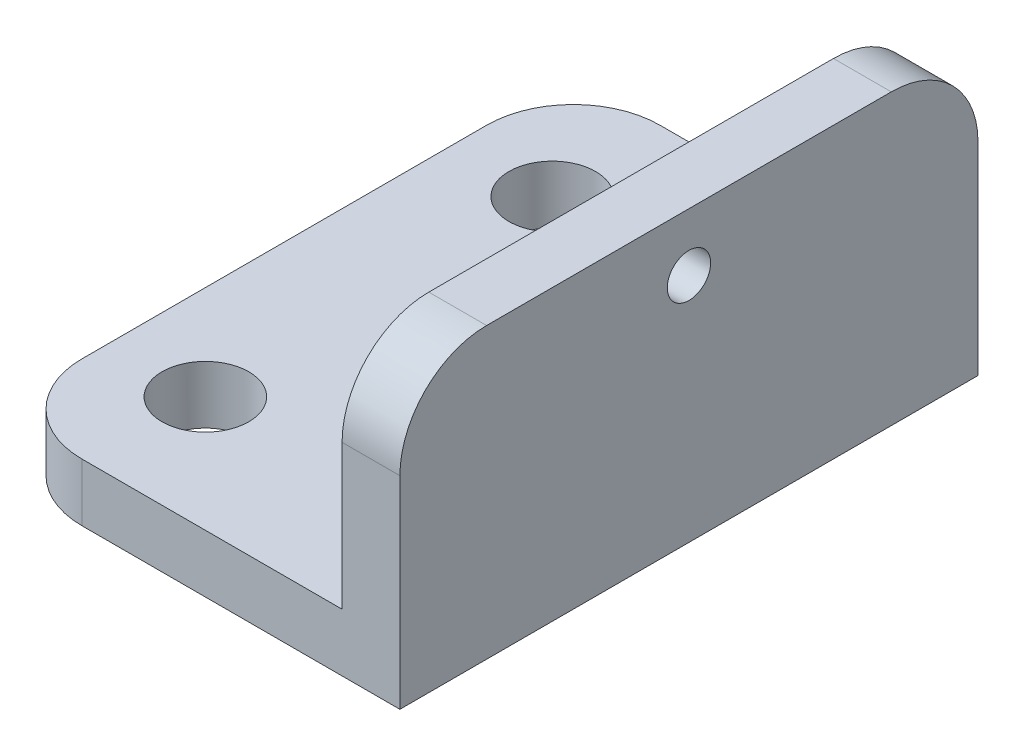
SolidWorks part; units mm, degrees
ref_plane "Front Plane" through (0, 0, 0) normal (0, 0, 1) x (1, 0, 0)
ref_plane "Top Plane" through (0, 0, 0) normal (0, 1, 0) x (1, 0, 0)
ref_plane "Right Plane" through (0, 0, 0) normal (1, 0, 0) x (0, 0, -1)
sketch "Sketch1" plane through (0, 0, 0) normal (0, 0, 1) x (1, 0, 0)
  line L0 (0, 0) -> (-12, 0)
  line L1 (0, 0) -> (0, 8)
  dimension "D1" = 8
  dimension "D2" = 12
extrude "Extrude-Thin1" add sketch "Sketch1" along normal mid plane 20 thin thin type one direction wall 2
fillet "Fillet2" radius 3 4 edges at (1, 8, 10) (1, 8, -10) (-12, -1, -10) (-12, -1, 10)
sketch "Sketch2" plane through (0, 0, 0) normal (0, 1, 0) x (1, 0, 0)
  line L0 (-12, -7) -> (-12, 7) construction
  line L1 (0, 0) -> (-12, 0) construction
  line L2 (0, -10) -> (0, 10) construction
  circle A0 centre (-8.729, 6) radius 1.5
  circle A1 centre (-8.729, -6) radius 1.5
  dimension "D1" = 3
  dimension "D2" = 3.271
  dimension "D3" = 6
extrude "Cut-Extrude1" cut sketch "Sketch2" against normal blind 10
sketch "Sketch3" plane through (0, 0, 0) normal (-1, 0, 0) x (0, 0, 1)
  line L0 (0, 0) -> (0, 8) construction
  line L1 (7, 8) -> (-7, 8) construction
  circle A0 centre (0, 6) radius 0.75
  dimension "D1" = 1.5
  dimension "D2" = 2
extrude "Cut-Extrude2" cut sketch "Sketch3" against normal blind 10
